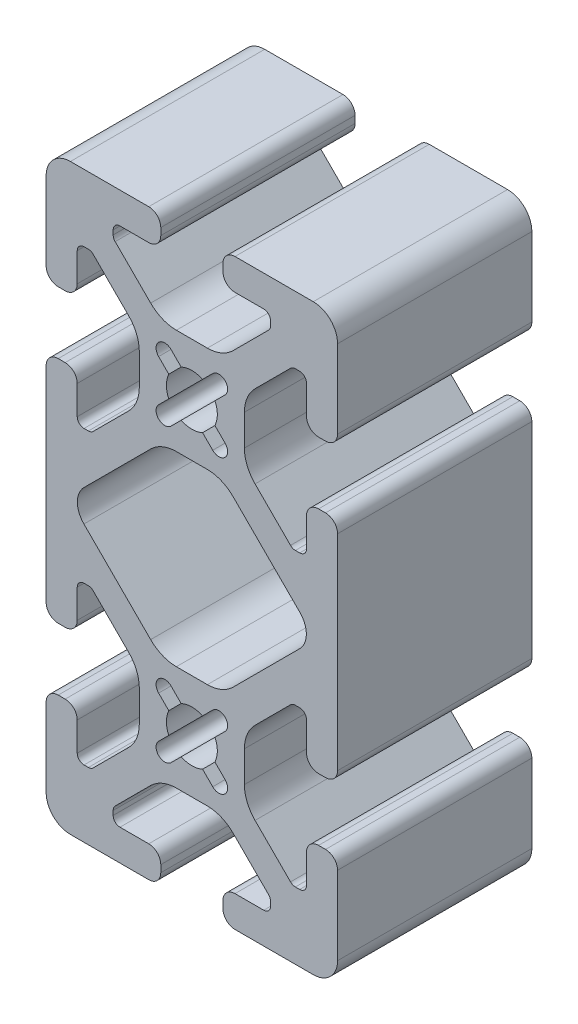
SolidWorks part; units mm, degrees
ref_plane "Front Plane" through (0, 0, 0) normal (0, 0, 1) x (1, 0, 0)
ref_plane "Top Plane" through (0, 0, 0) normal (0, 1, 0) x (1, 0, 0)
ref_plane "Right Plane" through (0, 0, 0) normal (1, 0, 0) x (0, 0, -1)
ref_plane "Plane1" through (0, 0, -25.4) normal (0, 0, -1) x (-1, 0, 0)
sketch "Sketch1" plane through (0, 0, -25.4) normal (0, 0, -1) x (-1, 0, 0)
  line L0 (5.3872, 29.8392) -> (14.1109, 21.1155)
  line L1 (14.1109, 16.9845) -> (5.3872, 8.2608)
  line L2 (2.0285, 6.8697) -> (-2.0285, 6.8697)
  line L3 (-5.3872, 8.2608) -> (-14.1109, 16.9845)
  line L4 (-14.1109, 21.1155) -> (-5.3872, 29.8392)
  line L5 (-2.0285, 31.2303) -> (2.0285, 31.2303)
  line L6 (1.4014, 3.0179) -> (2.7269, 4.3433)
  line L7 (4.3433, 2.7269) -> (3.0179, 1.4014)
  line L8 (3.0179, -1.4014) -> (4.3433, -2.7269)
  line L9 (2.7269, -4.3433) -> (1.4014, -3.0179)
  line L10 (-1.4014, -3.0179) -> (-2.7269, -4.3433)
  line L11 (-4.3433, -2.7269) -> (-3.0179, -1.4014)
  line L12 (-3.0179, 1.4014) -> (-4.3433, 2.7269)
  line L13 (-2.7269, 4.3433) -> (-1.4014, 3.0179)
  line L14 (3.0179, 36.6986) -> (4.3433, 35.3731)
  line L15 (2.7269, 33.7567) -> (1.4014, 35.0821)
  line L16 (-1.4014, 35.0821) -> (-2.7269, 33.7567)
  line L17 (-4.3433, 35.3731) -> (-3.0179, 36.6986)
  line L18 (-3.0179, 39.5014) -> (-4.3433, 40.8269)
  line L19 (-2.7269, 42.4433) -> (-1.4014, 41.1179)
  line L20 (1.4014, 41.1179) -> (2.7269, 42.4433)
  line L21 (4.3433, 40.8269) -> (3.0179, 39.5014)
  line L22 (17.4752, 34.036) -> (16.5608, 34.036)
  line L23 (14.986, 32.4612) -> (14.986, 28.702)
  line L24 (14.097, 27.813) -> (13.5289, 27.813)
  line L25 (12.9003, 28.0734) -> (8.2608, 32.7128)
  line L26 (6.8697, 36.0715) -> (6.8697, 40.1285)
  line L27 (8.2608, 43.4872) -> (12.9003, 48.1266)
  line L28 (13.5289, 48.387) -> (14.097, 48.387)
  line L29 (14.986, 47.498) -> (14.986, 43.7388)
  line L30 (16.5608, 42.164) -> (17.4752, 42.164)
  line L31 (19.05, 43.7388) -> (19.05, 53.975)
  line L32 (15.875, 57.15) -> (5.6388, 57.15)
  line L33 (4.064, 55.5752) -> (4.064, 54.6608)
  line L34 (5.6388, 53.086) -> (9.398, 53.086)
  line L35 (10.287, 52.197) -> (10.287, 51.6289)
  line L36 (10.0266, 51.0003) -> (5.3872, 46.3608)
  line L37 (2.0285, 44.9697) -> (-2.0285, 44.9697)
  line L38 (-5.3872, 46.3608) -> (-10.0266, 51.0003)
  line L39 (-10.287, 51.6289) -> (-10.287, 52.197)
  line L40 (-9.398, 53.086) -> (-5.6388, 53.086)
  line L41 (-4.064, 54.6608) -> (-4.064, 55.5752)
  line L42 (-5.6388, 57.15) -> (-15.875, 57.15)
  line L43 (-19.05, 53.975) -> (-19.05, 43.7388)
  line L44 (-17.4752, 42.164) -> (-16.5608, 42.164)
  line L45 (-14.986, 43.7388) -> (-14.986, 47.498)
  line L46 (-14.097, 48.387) -> (-13.5289, 48.387)
  line L47 (-12.9003, 48.1266) -> (-8.2608, 43.4872)
  line L48 (-6.8697, 40.1285) -> (-6.8697, 36.0715)
  line L49 (-8.2608, 32.7128) -> (-12.9003, 28.0734)
  line L50 (-13.5289, 27.813) -> (-14.097, 27.813)
  line L51 (-14.986, 28.702) -> (-14.986, 32.4612)
  line L52 (-16.5608, 34.036) -> (-17.4752, 34.036)
  line L53 (-19.05, 32.4612) -> (-19.05, 5.6388)
  line L54 (-17.4752, 4.064) -> (-16.5608, 4.064)
  line L55 (-14.986, 5.6388) -> (-14.986, 9.398)
  line L56 (-14.097, 10.287) -> (-13.5289, 10.287)
  line L57 (-12.9003, 10.0266) -> (-8.2608, 5.3872)
  line L58 (-6.8697, 2.0285) -> (-6.8697, -2.0285)
  line L59 (-8.2608, -5.3872) -> (-12.9003, -10.0266)
  line L60 (-13.5289, -10.287) -> (-14.097, -10.287)
  line L61 (-14.986, -9.398) -> (-14.986, -5.6388)
  line L62 (-16.5608, -4.064) -> (-17.4752, -4.064)
  line L63 (-19.05, -5.6388) -> (-19.05, -15.875)
  line L64 (-15.875, -19.05) -> (-5.6388, -19.05)
  line L65 (-4.064, -17.4752) -> (-4.064, -16.5608)
  line L66 (-5.6388, -14.986) -> (-9.398, -14.986)
  line L67 (-10.287, -14.097) -> (-10.287, -13.5289)
  line L68 (-10.0266, -12.9003) -> (-5.3872, -8.2608)
  line L69 (-2.0285, -6.8697) -> (2.0285, -6.8697)
  line L70 (5.3872, -8.2608) -> (10.0266, -12.9003)
  line L71 (10.287, -13.5289) -> (10.287, -14.097)
  line L72 (9.398, -14.986) -> (5.6388, -14.986)
  line L73 (4.064, -16.5608) -> (4.064, -17.4752)
  line L74 (5.6388, -19.05) -> (15.875, -19.05)
  line L75 (19.05, -15.875) -> (19.05, -5.6388)
  line L76 (17.4752, -4.064) -> (16.5608, -4.064)
  line L77 (14.986, -5.6388) -> (14.986, -9.398)
  line L78 (14.097, -10.287) -> (13.5289, -10.287)
  line L79 (12.9003, -10.0266) -> (8.2608, -5.3872)
  line L80 (6.8697, -2.0285) -> (6.8697, 2.0285)
  line L81 (8.2608, 5.3872) -> (12.9003, 10.0266)
  line L82 (13.5289, 10.287) -> (14.097, 10.287)
  line L83 (14.986, 9.398) -> (14.986, 5.6388)
  line L84 (16.5608, 4.064) -> (17.4752, 4.064)
  line L85 (19.05, 5.6388) -> (19.05, 32.4612)
  arc A0 (14.1109, 21.1155) -> (14.1109, 16.9845) centre (12.0454, 19.05) cw
  arc A1 (5.3872, 8.2608) -> (2.0285, 6.8697) centre (2.0285, 11.6195) cw
  arc A2 (-2.0285, 6.8697) -> (-5.3872, 8.2608) centre (-2.0285, 11.6195) cw
  arc A3 (-14.1109, 16.9845) -> (-14.1109, 21.1155) centre (-12.0454, 19.05) cw
  arc A4 (-5.3872, 29.8392) -> (-2.0285, 31.2303) centre (-2.0285, 26.4805) cw
  arc A5 (2.0285, 31.2303) -> (5.3872, 29.8392) centre (2.0285, 26.4805) cw
  arc A6 (2.7269, 4.3433) -> (4.3433, 2.7269) centre (3.5351, 3.5351) cw
  arc A7 (3.0179, 1.4014) -> (3.0179, -1.4014) centre (0, 0) cw
  arc A8 (4.3433, -2.7269) -> (2.7269, -4.3433) centre (3.5351, -3.5351) cw
  arc A9 (1.4014, -3.0179) -> (-1.4014, -3.0179) centre (0, 0) cw
  arc A10 (-2.7269, -4.3433) -> (-4.3433, -2.7269) centre (-3.5351, -3.5351) cw
  arc A11 (-3.0179, -1.4014) -> (-3.0179, 1.4014) centre (0, 0) cw
  arc A12 (-4.3433, 2.7269) -> (-2.7269, 4.3433) centre (-3.5351, 3.5351) cw
  arc A13 (-1.4014, 3.0179) -> (1.4014, 3.0179) centre (0, 0) cw
  arc A14 (4.3433, 35.3731) -> (2.7269, 33.7567) centre (3.5351, 34.5649) cw
  arc A15 (1.4014, 35.0821) -> (-1.4014, 35.0821) centre (0, 38.1) cw
  arc A16 (-2.7269, 33.7567) -> (-4.3433, 35.3731) centre (-3.5351, 34.5649) cw
  arc A17 (-3.0179, 36.6986) -> (-3.0179, 39.5014) centre (0, 38.1) cw
  arc A18 (-4.3433, 40.8269) -> (-2.7269, 42.4433) centre (-3.5351, 41.6351) cw
  arc A19 (-1.4014, 41.1179) -> (1.4014, 41.1179) centre (0, 38.1) cw
  arc A20 (2.7269, 42.4433) -> (4.3433, 40.8269) centre (3.5351, 41.6351) cw
  arc A21 (3.0179, 39.5014) -> (3.0179, 36.6986) centre (0, 38.1) cw
  arc A22 (19.05, 32.4612) -> (17.4752, 34.036) centre (17.4752, 32.4612) ccw
  arc A23 (16.5608, 34.036) -> (14.986, 32.4612) centre (16.5608, 32.4612) ccw
  arc A24 (14.986, 28.702) -> (14.097, 27.813) centre (14.097, 28.702) cw
  arc A25 (13.5289, 27.813) -> (12.9003, 28.0734) centre (13.5289, 28.702) cw
  arc A26 (8.2608, 32.7128) -> (6.8697, 36.0715) centre (11.6195, 36.0715) cw
  arc A27 (6.8697, 40.1285) -> (8.2608, 43.4872) centre (11.6195, 40.1285) cw
  arc A28 (12.9003, 48.1266) -> (13.5289, 48.387) centre (13.5289, 47.498) cw
  arc A29 (14.097, 48.387) -> (14.986, 47.498) centre (14.097, 47.498) cw
  arc A30 (14.986, 43.7388) -> (16.5608, 42.164) centre (16.5608, 43.7388) ccw
  arc A31 (17.4752, 42.164) -> (19.05, 43.7388) centre (17.4752, 43.7388) ccw
  arc A32 (19.05, 53.975) -> (15.875, 57.15) centre (15.875, 53.975) ccw
  arc A33 (5.6388, 57.15) -> (4.064, 55.5752) centre (5.6388, 55.5752) ccw
  arc A34 (4.064, 54.6608) -> (5.6388, 53.086) centre (5.6388, 54.6608) ccw
  arc A35 (9.398, 53.086) -> (10.287, 52.197) centre (9.398, 52.197) cw
  arc A36 (10.287, 51.6289) -> (10.0266, 51.0003) centre (9.398, 51.6289) cw
  arc A37 (5.3872, 46.3608) -> (2.0285, 44.9697) centre (2.0285, 49.7195) cw
  arc A38 (-2.0285, 44.9697) -> (-5.3872, 46.3608) centre (-2.0285, 49.7195) cw
  arc A39 (-10.0266, 51.0003) -> (-10.287, 51.6289) centre (-9.398, 51.6289) cw
  arc A40 (-10.287, 52.197) -> (-9.398, 53.086) centre (-9.398, 52.197) cw
  arc A41 (-5.6388, 53.086) -> (-4.064, 54.6608) centre (-5.6388, 54.6608) ccw
  arc A42 (-4.064, 55.5752) -> (-5.6388, 57.15) centre (-5.6388, 55.5752) ccw
  arc A43 (-15.875, 57.15) -> (-19.05, 53.975) centre (-15.875, 53.975) ccw
  arc A44 (-19.05, 43.7388) -> (-17.4752, 42.164) centre (-17.4752, 43.7388) ccw
  arc A45 (-16.5608, 42.164) -> (-14.986, 43.7388) centre (-16.5608, 43.7388) ccw
  arc A46 (-14.986, 47.498) -> (-14.097, 48.387) centre (-14.097, 47.498) cw
  arc A47 (-13.5289, 48.387) -> (-12.9003, 48.1266) centre (-13.5289, 47.498) cw
  arc A48 (-8.2608, 43.4872) -> (-6.8697, 40.1285) centre (-11.6195, 40.1285) cw
  arc A49 (-6.8697, 36.0715) -> (-8.2608, 32.7128) centre (-11.6195, 36.0715) cw
  arc A50 (-12.9003, 28.0734) -> (-13.5289, 27.813) centre (-13.5289, 28.702) cw
  arc A51 (-14.097, 27.813) -> (-14.986, 28.702) centre (-14.097, 28.702) cw
  arc A52 (-14.986, 32.4612) -> (-16.5608, 34.036) centre (-16.5608, 32.4612) ccw
  arc A53 (-17.4752, 34.036) -> (-19.05, 32.4612) centre (-17.4752, 32.4612) ccw
  arc A54 (-19.05, 5.6388) -> (-17.4752, 4.064) centre (-17.4752, 5.6388) ccw
  arc A55 (-16.5608, 4.064) -> (-14.986, 5.6388) centre (-16.5608, 5.6388) ccw
  arc A56 (-14.986, 9.398) -> (-14.097, 10.287) centre (-14.097, 9.398) cw
  arc A57 (-13.5289, 10.287) -> (-12.9003, 10.0266) centre (-13.5289, 9.398) cw
  arc A58 (-8.2608, 5.3872) -> (-6.8697, 2.0285) centre (-11.6195, 2.0285) cw
  arc A59 (-6.8697, -2.0285) -> (-8.2608, -5.3872) centre (-11.6195, -2.0285) cw
  arc A60 (-12.9003, -10.0266) -> (-13.5289, -10.287) centre (-13.5289, -9.398) cw
  arc A61 (-14.097, -10.287) -> (-14.986, -9.398) centre (-14.097, -9.398) cw
  arc A62 (-14.986, -5.6388) -> (-16.5608, -4.064) centre (-16.5608, -5.6388) ccw
  arc A63 (-17.4752, -4.064) -> (-19.05, -5.6388) centre (-17.4752, -5.6388) ccw
  arc A64 (-19.05, -15.875) -> (-15.875, -19.05) centre (-15.875, -15.875) ccw
  arc A65 (-5.6388, -19.05) -> (-4.064, -17.4752) centre (-5.6388, -17.4752) ccw
  arc A66 (-4.064, -16.5608) -> (-5.6388, -14.986) centre (-5.6388, -16.5608) ccw
  arc A67 (-9.398, -14.986) -> (-10.287, -14.097) centre (-9.398, -14.097) cw
  arc A68 (-10.287, -13.5289) -> (-10.0266, -12.9003) centre (-9.398, -13.5289) cw
  arc A69 (-5.3872, -8.2608) -> (-2.0285, -6.8697) centre (-2.0285, -11.6195) cw
  arc A70 (2.0285, -6.8697) -> (5.3872, -8.2608) centre (2.0285, -11.6195) cw
  arc A71 (10.0266, -12.9003) -> (10.287, -13.5289) centre (9.398, -13.5289) cw
  arc A72 (10.287, -14.097) -> (9.398, -14.986) centre (9.398, -14.097) cw
  arc A73 (5.6388, -14.986) -> (4.064, -16.5608) centre (5.6388, -16.5608) ccw
  arc A74 (4.064, -17.4752) -> (5.6388, -19.05) centre (5.6388, -17.4752) ccw
  arc A75 (15.875, -19.05) -> (19.05, -15.875) centre (15.875, -15.875) ccw
  arc A76 (19.05, -5.6388) -> (17.4752, -4.064) centre (17.4752, -5.6388) ccw
  arc A77 (16.5608, -4.064) -> (14.986, -5.6388) centre (16.5608, -5.6388) ccw
  arc A78 (14.986, -9.398) -> (14.097, -10.287) centre (14.097, -9.398) cw
  arc A79 (13.5289, -10.287) -> (12.9003, -10.0266) centre (13.5289, -9.398) cw
  arc A80 (8.2608, -5.3872) -> (6.8697, -2.0285) centre (11.6195, -2.0285) cw
  arc A81 (6.8697, 2.0285) -> (8.2608, 5.3872) centre (11.6195, 2.0285) cw
  arc A82 (12.9003, 10.0266) -> (13.5289, 10.287) centre (13.5289, 9.398) cw
  arc A83 (14.097, 10.287) -> (14.986, 9.398) centre (14.097, 9.398) cw
  arc A84 (14.986, 5.6388) -> (16.5608, 4.064) centre (16.5608, 5.6388) ccw
  arc A85 (17.4752, 4.064) -> (19.05, 5.6388) centre (17.4752, 5.6388) ccw
extrude "Boss-Extrude1" add sketch "Sketch1" against normal blind 25.4
